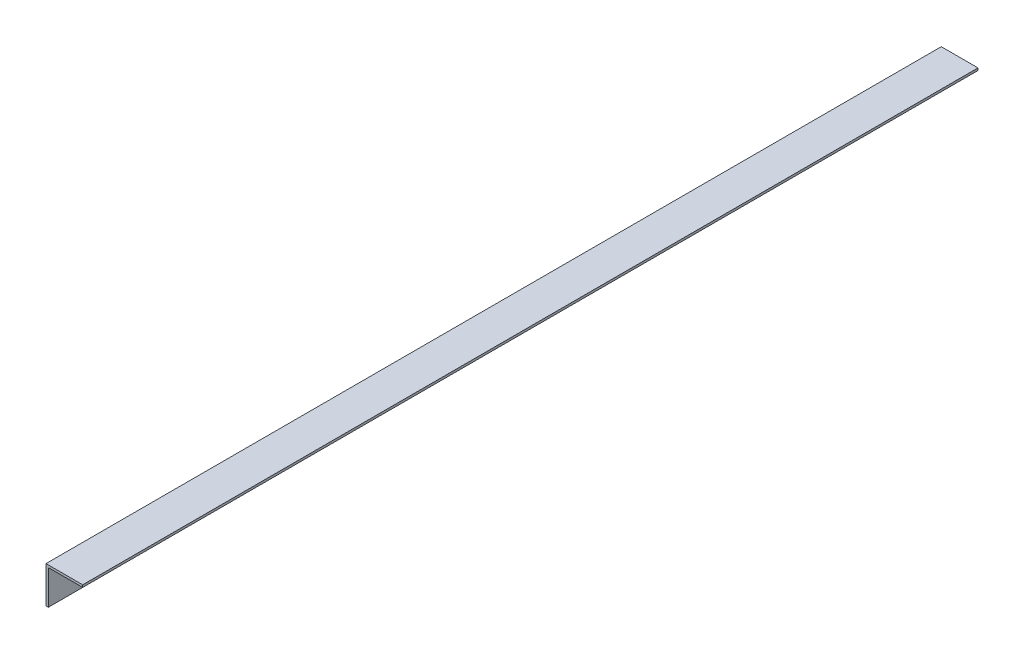
SolidWorks part; units mm, degrees
ref_plane "Front Plane" through (0, 0, 0) normal (0, 0, 1) x (1, 0, 0)
ref_plane "Top Plane" through (0, 0, 0) normal (0, 1, 0) x (1, 0, 0)
ref_plane "Right Plane" through (0, 0, 0) normal (1, 0, 0) x (0, 0, -1)
other "Configuration Table"
sketch "Sketch1" plane through (0, 0, 0) normal (0, 0, 1) x (1, 0, 0)
  line L0 (38, 1042) -> (40, 1042)
  line L1 (40, 1042) -> (40, 1072)
  line L2 (40, 1072) -> (70, 1072)
  line L3 (70, 1072) -> (70, 1074)
  line L4 (70, 1074) -> (38, 1074)
  line L5 (38, 1074) -> (38, 1042)
extrude "PRESS_tepsi_rafi_kosebent_sol_1" add sketch "Sketch1" against normal blind 780 from offset 20 separate body
